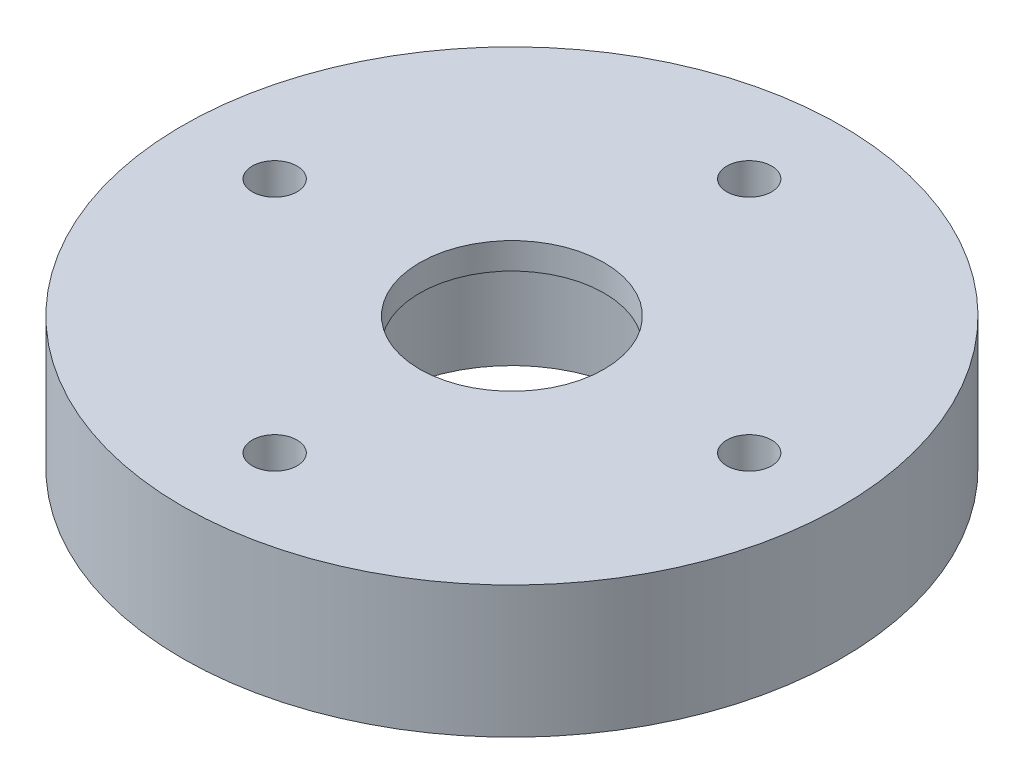
SolidWorks part; units mm, degrees
ref_plane "Front Plane" through (0, 0, 0) normal (0, 0, 1) x (1, 0, 0)
ref_plane "Top Plane" through (0, 0, 0) normal (0, 1, 0) x (1, 0, 0)
ref_plane "Right Plane" through (0, 0, 0) normal (1, 0, 0) x (0, 0, -1)
sketch "Sketch1" plane through (0, 0, 0) normal (0, 1, 0) x (1, 0, 0)
  circle A0 centre (0, 0) radius 25
  circle A1 centre (0, 0) radius 7
  circle A3 centre (0, 18) radius 1.7
  circle A4 centre (18, 0) radius 1.7
  circle A5 centre (0, -18) radius 1.7
  circle A6 centre (-18, 0) radius 1.7
  point P16 (0, 0)
  dimension "D1" = 4
extrude "Boss-Extrude1" add sketch "Sketch1" along normal blind 10
sketch "Sketch2" plane through (0, 0, 0) normal (0, -1, 0) x (1, 0, 0)
  circle A0 centre (0, 0) radius 9.53
extrude "Cut-Extrude1" cut sketch "Sketch2" against normal blind 8
sketch "Sketch4" plane through (0, 0, 0) normal (0, -1, 0) x (1, 0, 0)
  circle A1 centre (0, 18) radius 3
  circle A2 centre (-18, 0) radius 3
  circle A3 centre (0, -18) radius 3
  circle A4 centre (18, 0) radius 3
  dimension "D1" = 6
extrude "Cut-Extrude2" cut sketch "Sketch4" against normal blind 7
